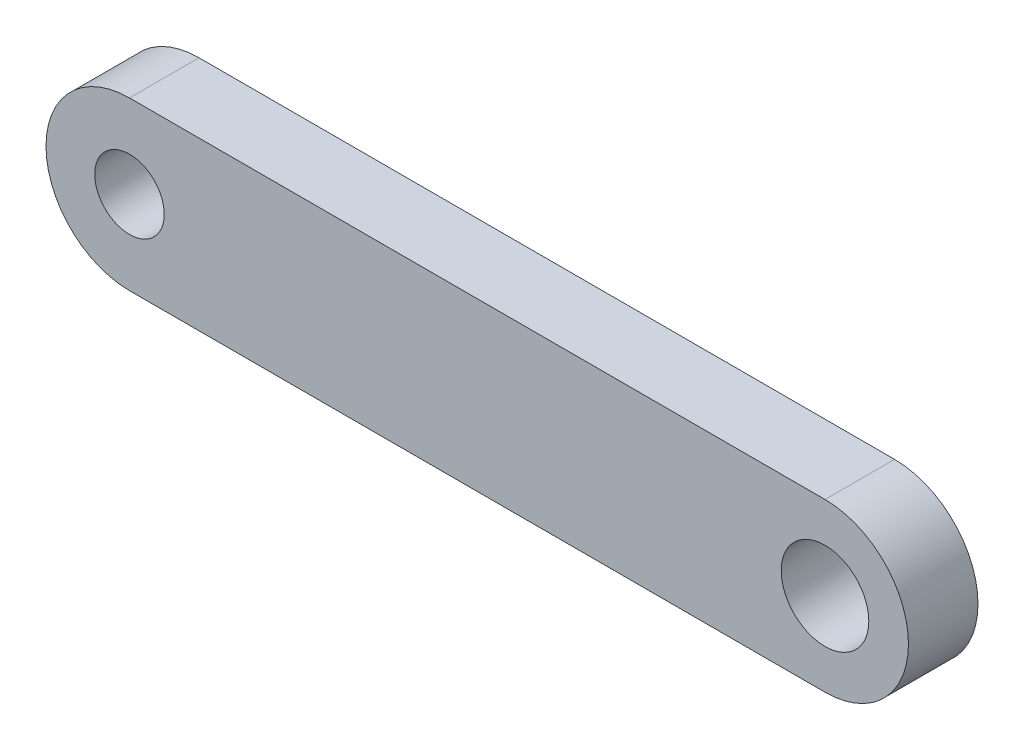
SolidWorks part; units mm, degrees
ref_plane "Front Plane" through (0, 0, 0) normal (0, 0, 1) x (1, 0, 0)
ref_plane "Top Plane" through (0, 0, 0) normal (0, 1, 0) x (1, 0, 0)
ref_plane "Right Plane" through (0, 0, 0) normal (1, 0, 0) x (0, 0, -1)
sketch "Sketch1" plane through (0, 0, 0) normal (0, 0, 1) x (1, 0, 0)
  line L1 (0, 0) -> (50, 0)
  line L2 (0, 0) -> (0, 12)
  line L3 (0, 12) -> (50, 12)
  line L4 (50, 0) -> (50, 12)
  arc A0 (0, 12) -> (0, 0) centre (0, 6) ccw
  arc A1 (50, 0) -> (50, 12) centre (50, 6) ccw
  circle A2 centre (0, 6) radius 2.5
  circle A3 centre (50, 6) radius 3.15
  dimension "D1" = 12
  dimension "D3" = 5
  dimension "D4" = 6.3
  dimension "D2" = 50
extrude "Boss-Extrude1" add sketch "Sketch1" along normal blind 5 contours A3 L4 L3 L2 A2 L1 | A2 L2 A0 | A3 L4 A1
